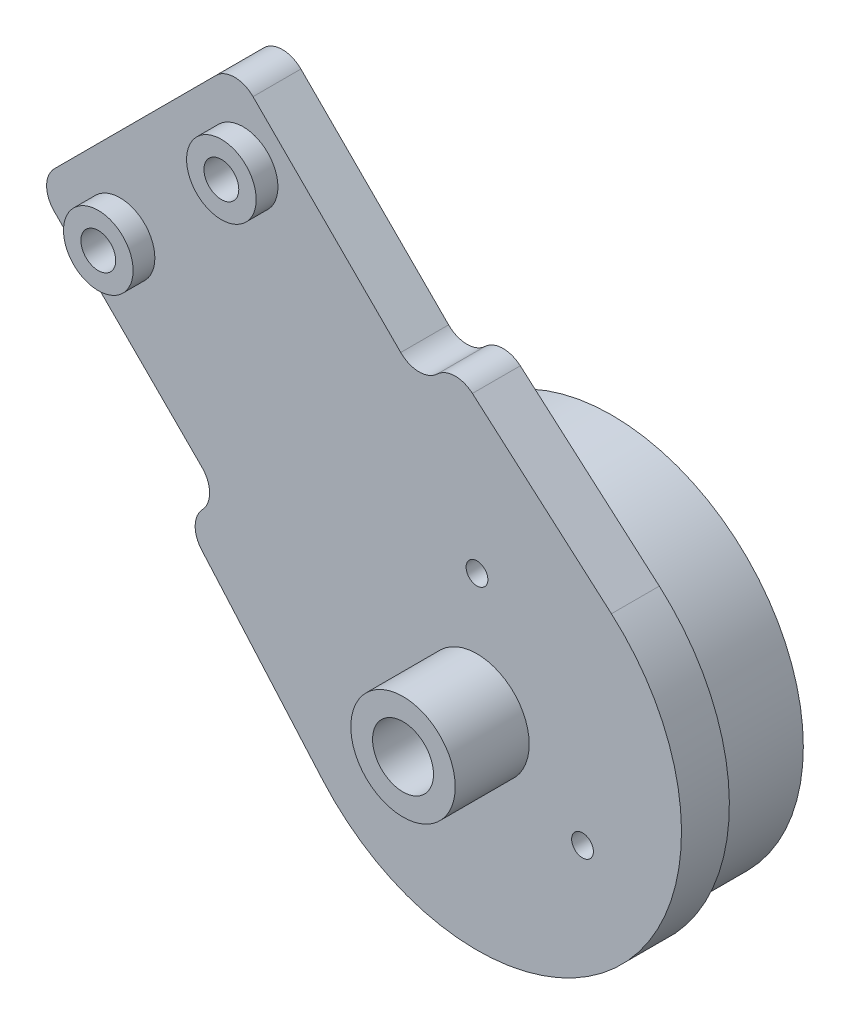
SolidWorks part; units mm, degrees
ref_plane "Front Plane" through (0, 0, 0) normal (0, 0, 1) x (1, 0, 0)
ref_plane "Top Plane" through (0, 0, 0) normal (0, 1, 0) x (1, 0, 0)
ref_plane "Right Plane" through (0, 0, 0) normal (1, 0, 0) x (0, 0, -1)
sketch "Sketch1" plane through (0, 0, 0) normal (0, 0, 1) x (1, 0, 0)
  line L0 (-106.0307, 0) -> (93.9693, 0) construction
  line L1 (-106.0307, 0) -> (-6.0307, 100) construction
  line L2 (-6.0307, 100) -> (93.9693, 0) construction
  line L3 (0, 0) -> (-53.0154, 53.0154) construction
  line L4 (-46.0307, 60) -> (33.9693, 60) construction
  line L5 (-6.0307, 100) -> (-6.0307, 60) construction
  circle A0 centre (-106.0307, 0) radius 20
  circle A1 centre (0, 0) radius 20
  circle A2 centre (93.9693, 0) radius 20
  dimension "D6" = 40
  dimension "D7" = 40
  dimension "D8" = 40
  dimension "D1" = 200
  dimension "D2" = 90
  dimension "D3" = 90
  dimension "D4" = 80
  dimension "D5" = 40
sketch "Sketch2" plane through (0, 0, 0) normal (0, 0, 1) x (1, 0, 0)
  line L0 (-62.5472, 43.4835) -> (-46.0307, 60) construction
  line L2 (-106.0307, 0) -> (-6.0307, 100) construction
  line L3 (-46.0307, 60) -> (33.9693, 60) construction
  line L4 (33.9693, 60) -> (80.5342, 13.435) construction
  line L5 (-6.0307, 100) -> (93.9693, 0) construction
  line L6 (-55.4762, 36.4124) -> (-41.8886, 50)
  line L7 (-41.8886, 50) -> (29.8271, 50)
  line L8 (29.8271, 50) -> (73.4632, 6.364)
  line L9 (-69.6183, 50.5546) -> (-50.1729, 70)
  line L10 (-50.1729, 70) -> (38.1114, 70)
  line L11 (38.1114, 70) -> (87.6053, 20.5061)
  line L12 (-55.4762, 36.4124) -> (-69.6183, 50.5546)
  line L13 (87.6053, 20.5061) -> (73.4632, 6.364)
  line L14 (98.8369, 5.0305) -> (85.2636, 18.1644)
  line L15 (88.8813, -4.8075) -> (76.0143, 8.8101)
  line L16 (85.2636, 18.1644) -> (76.0143, 8.8101)
  line L17 (84.0698, 24.0416) -> (69.9276, 9.8995) construction
  line L18 (-6.0307, 100) -> (-6.0307, 60) construction
  line L19 (-9.5307, 84.85) -> (-12.0307, 70)
  line L20 (-6.0307, 70) -> (-6.0307, 82.2198) construction
  line L21 (-2.5307, 84.85) -> (-0.0307, 70)
  circle A0 centre (93.9693, 0) radius 10 construction
  circle A1 centre (93.9693, 0) radius 3.5
  arc A2 (88.8813, -4.8075) -> (98.8369, 5.0305) centre (93.9693, 0) ccw
  circle A3 centre (93.9693, 0) radius 20 construction
  circle A4 centre (73.4632, 13.435) radius 1
  circle A5 centre (80.5342, 20.5061) radius 1
  circle A6 centre (-6.0307, 60) radius 1.5
  circle A7 centre (-6.0307, 84.85) radius 1.5
  arc A8 (-2.5307, 84.85) -> (-9.5307, 84.85) centre (-6.0307, 84.85) ccw
  circle A9 centre (-53.0154, 53.0154) radius 1.5
  point P45 (-6.0307, 70)
  dimension "D4" = 20
  dimension "D5" = 7
  dimension "D6" = 3
  dimension "D8" = 5
  dimension "D9" = 2
  dimension "D10" = 2
  dimension "D13" = 3
  dimension "D14" = 3
  dimension "D16" = 2
  dimension "D18" = 3
  dimension "D1" = 10
  dimension "D3" = 27.5
  dimension "D7" = 19
  dimension "D11" = 5
  dimension "D12" = 5
  dimension "D15" = 14.85
  dimension "D17" = 6
  dimension "D2" = 10
sketch "Sketch3" plane through (0, 0, 0) normal (0, 0, 1) x (1, 0, 0)
  line L0 (-94.5203, 11.5104) -> (-53.0154, 53.0154) construction
  line L1 (-106.0307, 0) -> (-6.0307, 100) construction
  line L2 (-53.0154, 53.0154) -> (-13.435, 13.435) construction
  line L3 (0, 0) -> (-53.0154, 53.0154) construction
  line L4 (-85.5246, 6.364) -> (-53.0154, 38.8732)
  line L5 (-53.0154, 38.8732) -> (-20.5061, 6.364)
  line L6 (-99.6668, 20.5061) -> (-53.0154, 67.1575)
  line L7 (-53.0154, 67.1575) -> (-6.364, 20.5061)
  line L8 (-95.851, 10.1797) -> (-53.0154, 53.0154) construction
  line L9 (-99.6668, 20.5061) -> (-85.5246, 6.364)
  line L10 (-20.5061, 6.364) -> (-6.364, 20.5061)
  line L11 (-102.9221, 17.2507) -> (-53.0154, 67.1575) construction
  line L12 (-88.78, 3.1086) -> (-53.0154, 38.8732) construction
  line L13 (-110.4492, 4.7673) -> (-96.685, 17.5243)
  line L14 (-106.0307, 0) -> (-96.685, 9.3457) construction
  line L15 (-101.2634, -4.4185) -> (-88.5064, 9.3457)
  line L16 (0, 0) -> (-13.435, 13.435) construction
  line L17 (-4.7673, -4.4185) -> (-17.5243, 9.3457)
  line L18 (4.4185, 4.7673) -> (-9.3457, 17.5243)
  line L19 (-96.1312, 24.0416) -> (-81.9891, 9.8995) construction
  line L20 (-9.8995, 24.0416) -> (-24.0416, 9.8995) construction
  circle A0 centre (-106.0307, 0) radius 10 construction
  circle A1 centre (-106.0307, 0) radius 3.5
  circle A2 centre (0, 0) radius 10 construction
  circle A4 centre (93.9693, 0) radius 10 construction
  circle A6 centre (0, 0) radius 3.5
  circle A7 centre (93.9693, 0) radius 3.5
  circle A8 centre (-106.0307, 0) radius 6.5
  circle A9 centre (0, 0) radius 6.5
  circle A10 centre (93.9693, 0) radius 6.5
  circle A11 centre (-92.5957, 20.5061) radius 1
  circle A12 centre (-85.5246, 13.435) radius 1
  circle A13 centre (-13.435, 20.5061) radius 1
  circle A14 centre (-20.5061, 13.435) radius 1
  circle A16 centre (-53.0154, 53.0154) radius 1.5 construction
  circle A17 centre (-53.0154, 53.0154) radius 1.5
  dimension "D1" = 20
  dimension "D2" = 20
  dimension "D3" = 20
  dimension "D4" = 7
  dimension "D5" = 7
  dimension "D6" = 7
  dimension "D7" = 3
  dimension "D8" = 3
  dimension "D9" = 3
  dimension "D14" = 2
  dimension "D15" = 2
  dimension "D16" = 2
  dimension "D17" = 2
  dimension "D10" = 10
  dimension "D12" = 19
  dimension "D13" = 19
  dimension "D18" = 5
  dimension "D19" = 5
  dimension "D20" = 5
  dimension "D21" = 5
  dimension "D22" = 5
  dimension "D23" = 5
  dimension "D11" = 10
sketch "Sketch4" plane through (0, 0, 0) normal (0, 0, 1) x (1, 0, 0)
  line L0 (-62.7556, 93.8025) -> (52.2444, 93.8025)
  line L1 (52.2444, 93.8025) -> (52.2444, 83.8025)
  line L2 (52.2444, 83.8025) -> (38.1114, 70)
  line L3 (-50.1729, 70) -> (38.1114, 70) construction
  line L4 (38.1114, 70) -> (-54.4235, 70)
  line L5 (-54.4235, 70) -> (-62.7556, 83.8025)
  line L6 (-62.7556, 83.8025) -> (-62.7556, 93.8025)
  line L7 (-2.0307, 60) -> (-2.0307, 70)
  line L8 (-10.0307, 60) -> (-10.0307, 70)
  line L9 (-28.5307, 85.3025) -> (16.4693, 85.3025) construction
  line L10 (-6.0307, 100) -> (-6.0307, 60) construction
  line L12 (-28.5307, 89.8025) -> (16.4693, 89.8025)
  line L13 (-28.5307, 80.8025) -> (16.4693, 80.8025)
  circle A0 centre (-6.0307, 60) radius 1.5 construction
  circle A1 centre (-6.0307, 60) radius 1.5
  arc A2 (-10.0307, 60) -> (-2.0307, 60) centre (-6.0307, 60) ccw
  circle A4 centre (-6.0307, 60) radius 4 construction
  arc A5 (-28.5307, 89.8025) -> (-28.5307, 80.8025) centre (-28.5307, 85.3025) ccw
  arc A6 (16.4693, 80.8025) -> (16.4693, 89.8025) centre (16.4693, 85.3025) ccw
  point P18 (-2.0307, 60)
  point P24 (-6.0307, 85.3025)
  dimension "D1" = 115
  dimension "D2" = 10
  dimension "D4" = 45
  dimension "D5" = 9
  dimension "D6" = 4
  dimension "D3" = 2.5
sketch "Sketch5" plane through (0, 0, 0) normal (0, 0, 1) x (1, 0, 0)
  line L0 (80.0423, 25.3467) -> (68.6226, 13.927)
  line L1 (68.6226, 13.927) -> (79.2292, 3.3204)
  line L2 (79.2292, 3.3204) -> (77.2263, 1.3175)
  line L3 (77.2263, 1.3175) -> (85.1154, -7.7248)
  line L4 (87.6053, 20.5061) -> (73.4632, 6.364) construction
  line L5 (93.9693, 0) -> (82.6825, 11.2867) construction
  line L6 (-6.0307, 100) -> (93.9693, 0) construction
  line L7 (90.6489, 14.7401) -> (92.6518, 16.743)
  line L8 (92.6518, 16.743) -> (101.694, 8.8538)
  line L9 (80.0423, 25.3467) -> (90.6489, 14.7401)
  circle A0 centre (93.9693, 0) radius 10 construction
  circle A1 centre (93.9693, 0) radius 10
  arc A2 (85.1154, -7.7248) -> (101.694, 8.8538) centre (93.9693, 0) ccw
  circle A3 centre (80.5342, 20.5061) radius 1 construction
  circle A4 centre (73.4632, 13.435) radius 1 construction
  circle A5 centre (80.5342, 20.5061) radius 1
  circle A6 centre (73.4632, 13.435) radius 1
  circle A8 centre (93.9693, 0) radius 11.75 construction
  point P25 (105.7193, 0)
  dimension "D3" = 12
  dimension "D4" = 15
  dimension "D1" = 1.75
extrude "Boss-Extrude1" add sketch "Sketch5" along normal blind 2.75
sketch "Sketch6" plane through (0, 0, 2.75) normal (0, 0, 1) x (1, 0, 0)
  circle A0 centre (93.9693, 0) radius 10 construction
  circle A1 centre (93.9693, 0) radius 10
extrude "Boss-Extrude2" add sketch "Sketch6" against normal blind 1
sketch "Sketch7" plane through (0, 0, 0) normal (0, 0, -1) x (-1, 0, 0)
  circle A1 centre (-93.9693, 0) radius 10 construction
  circle A2 centre (-93.9693, 0) radius 11
  circle A3 centre (-93.9693, 0) radius 11
  circle A4 centre (-93.9693, 0) radius 10
  dimension "D1" = 1
extrude "Boss-Extrude3" add sketch "Sketch7" along normal blind 5
fillet "Fillet3" radius 1.5 4 edges at (90.6489, 14.7401, 1.375) (79.2292, 3.3204, 1.375) (68.6226, 13.927, 1.375) (80.0423, 25.3467, 1.375)
fillet "Fillet4" radius 1.5 2 edges at (77.2263, 1.3175, 1.375) (92.6518, 16.743, 1.375)
sketch "Sketch8" plane through (0, 0, 2.75) normal (0, 0, 1) x (1, 0, 0)
  circle A10 centre (73.4632, 13.435) radius 2
  circle A11 centre (73.4632, 13.435) radius 2
  circle A12 centre (73.4632, 13.435) radius 1
  circle A13 centre (80.5342, 20.5061) radius 2
  circle A14 centre (80.5342, 20.5061) radius 2
  circle A15 centre (80.5342, 20.5061) radius 1
  dimension "D1" = 1
  dimension "D2" = 1
extrude "Boss-Extrude4" add sketch "Sketch8" along normal blind 1.25
sketch "Sketch10" plane through (0, 0, 2.75) normal (0, 0, 1) x (1, 0, 0)
  line L0 (82.6825, 11.2867) -> (93.9693, 0) construction
  circle A0 centre (93.9693, 0) radius 1.75
  dimension "D1" = 3.5
extrude "Cut-Extrude1" cut sketch "Sketch10" against normal up to surface (1 mm away) up to face at (103.9693, 0, 1.75)
sketch "Sketch11" plane through (0, 0, 2.75) normal (0, 0, 1) x (1, 0, 0)
  circle A0 centre (93.9693, 0) radius 1.75 construction
  circle A1 centre (93.9693, 0) radius 1.75
  circle A2 centre (93.9693, 0) radius 3
  dimension "D1" = 6
extrude "Boss-Extrude5" add sketch "Sketch11" along normal blind 4.25
sketch "Sketch12" plane through (0, 0, 2.75) normal (0, 0, 1) x (1, 0, 0)
  line L0 (93.9693, 0) -> (93.9693, 7) construction
  circle A0 centre (93.9693, 7) radius 0.625
  circle A1 centre (100.0315, -3.5) radius 0.625
  circle A2 centre (87.9071, -3.5) radius 0.625
  dimension "D1" = 1.25
  dimension "D2" = 7
  dimension "D3" = 3
extrude "Cut-Extrude2" cut sketch "Sketch12" against normal blind 4.25
